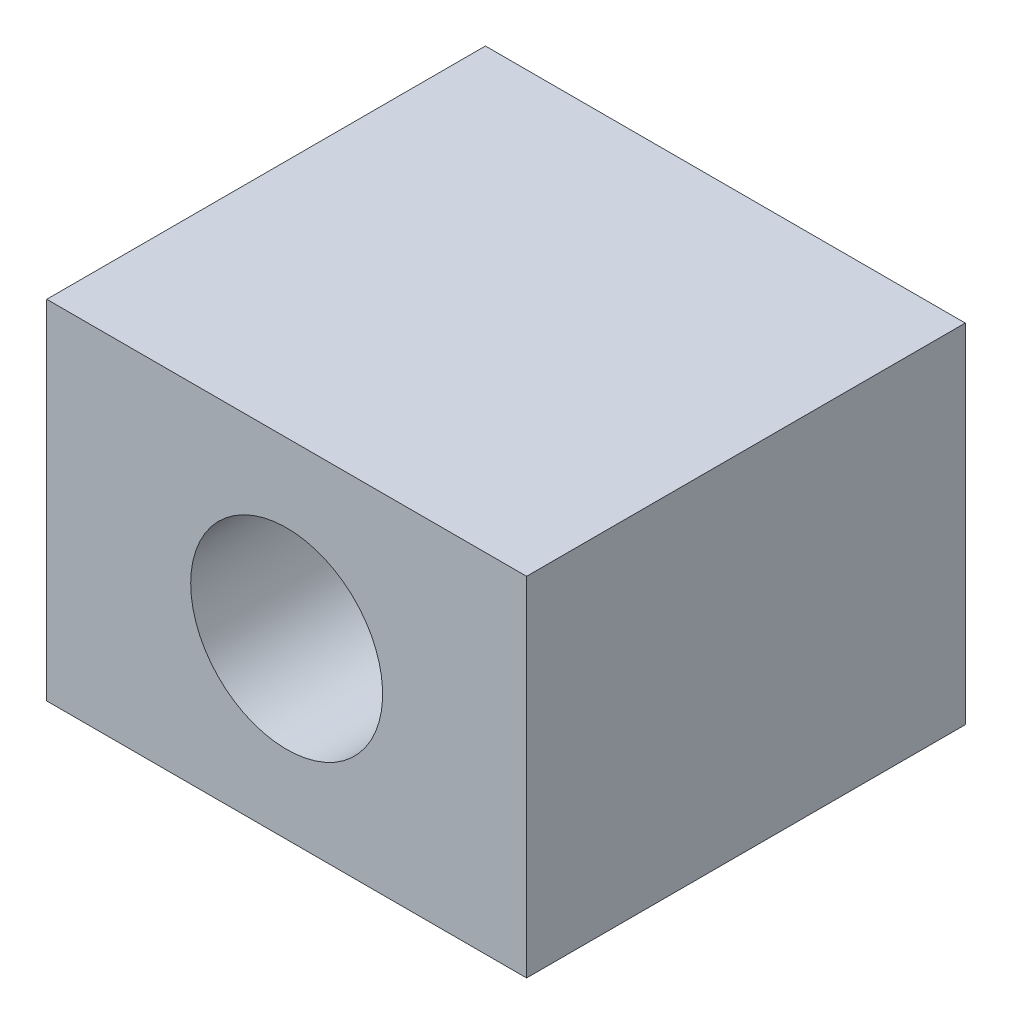
SolidWorks part; units mm, degrees
ref_plane "前视基准面" through (0, 0, 0) normal (0, 0, 1) x (1, 0, 0)
ref_plane "上视基准面" through (0, 0, 0) normal (0, 1, 0) x (1, 0, 0)
ref_plane "右视基准面" through (0, 0, 0) normal (1, 0, 0) x (0, 0, -1)
sketch "草图1" plane through (0, 0, 0) normal (0, 1, 0) x (1, 0, 0)
  circle A0 centre (0, 0) radius 15
  dimension "D1" = 30
extrude "凸台-拉伸1" add sketch "草图1" along normal blind 5
sketch "草图2" plane through (0, 5, 0) normal (0, 1, 0) x (1, 0, 0)
  circle A0 centre (0, 0) radius 12 construction
  point P4 (0, 12)
  point P6 (0, -12)
  point P8 (-12, 0)
  point P10 (12, 0)
  dimension "D1" = 24
hole_wizard "M3 螺纹孔的螺纹孔钻头1" positions "草图2" profile "草图3" hole size "M3" standard "GB" end condition up to next
sketch "草图3" plane through (12, 5, 0) normal (1, 0, 0) x (0, 0, 1)
  line L0 (0, 0) -> (0, 5)
  line L1 (0, 5) -> (1.25, 5)
  line L2 (1.25, 5) -> (1.25, 0)
  line L5 (1.25, 0) -> (0, 0)
  line L11 (0, -6.35) -> (0, 107.95) construction
  dimension "通孔孔直径" = 2.5
  dimension "通孔孔深度" = 5
sketch "草图4" plane through (0, 5, 0) normal (0, 1, 0) x (1, 0, 0)
  circle A0 centre (0, 0) radius 6
  dimension "D1" = 12
extrude "凸台-拉伸2" add sketch "草图4" along normal blind 10
sketch "草图5" plane through (0, 15, 0) normal (0, 1, 0) x (1, 0, 0)
  circle A0 centre (0, 0) radius 2.5
  dimension "D1" = 5
extrude "切除-拉伸1" cut sketch "草图5" against normal through all
fillet "圆角1" radius 0.5 1 edges at (0, 5, 6)
sketch "草图6" plane through (0, 0, 0) normal (0, 0, 1) x (1, 0, 0)
  line L0 (-2, 8.1) -> (2, 8.1)
  line L1 (2, 8.1) -> (2, 11)
  line L2 (2, 11) -> (-2, 11)
  line L3 (0, 11) -> (0, 8.1) construction
  line L5 (2.5, 15) -> (-2.5, 15) construction
  line L7 (-2, 8.1) -> (-2, 11)
  dimension "D1" = 2
  dimension "D2" = 2.9
  dimension "D3" = 4
extrude "切除-拉伸3" cut sketch "草图6" against normal through all flip side to cut contours L1 L2 L7 L0
sketch "草图7" plane through (0, 11, 0) normal (0, 1, 0) x (1, 0, 0)
  line L0 (2, 1.5) -> (-2, 1.5)
  line L1 (-2, 1.5) -> (-2, 2.8083)
  line L2 (-2, 5.6569) -> (-2, 1.5) construction
  line L3 (-2, 2.8083) -> (2, 2.8083)
  line L4 (2, 5.6569) -> (2, 1.5) construction
  line L5 (2, 2.8083) -> (2, 1.5)
  line L6 (0, 1.5) -> (0, 2.8083) construction
  dimension "D1" = 1.5
  dimension "D2" = 1.3083
  dimension "D3" = 1.3083
extrude "凸台-拉伸3" add sketch "草图7" against normal through all contours L3 L5 L0 L1
sketch "草图9" plane through (0, 0, -1.5) normal (0, 0, 1) x (1, 0, 0)
  line L0 (2, 8.1) -> (-2, 11) construction
  line L1 (2, 11) -> (-2, 8.1) construction
hole_wizard "M2 螺纹孔的螺纹孔钻头1" positions "草图10" profile "草图11" hole size "M2" standard "GB" end condition through all
sketch "草图10" plane through (0, 0, -1.5) normal (0, 0, 1) x (1, 0, 0)
  line L0 (2, 8.1) -> (-2, 11) construction
  point P1 (0, 9.55)
sketch "草图11" plane through (0, 9.55, -1.5) normal (1, 0, 0) x (0, -1, 0)
  line L0 (0, 0) -> (0, 4.5)
  line L1 (0, 4.5) -> (0.8, 4.5)
  line L2 (0.8, 4.5) -> (0.8, 0)
  line L5 (0.8, 0) -> (0, 0)
  line L11 (0, -6.35) -> (0, 107.95) construction
  dimension "通孔孔直径" = 1.6
  dimension "通孔孔深度" = 4.5
sketch "草图12" plane through (0, 8.1, 0) normal (0, -1, 0) x (1, 0, 0)
  line L1 (-2, -1.5) -> (2, -1.5)
  line L2 (-2, -1.5) -> (-2, -5.6569)
  line L3 (-2, -5.6569) -> (2, -5.6569)
  line L4 (2, -1.5) -> (2, -5.6569)
extrude "切除-拉伸4" cut sketch "草图12" against normal through all flip side to cut
sketch "草图13" plane through (0, 8.1, 0) normal (0, -1, 0) x (1, 0, 0)
  line L0 (2, -5.6569) -> (2, -1.5) construction
  line L1 (-2, -1.5) -> (2, -1.5)
  line L2 (-2, -1.5) -> (-2, -2)
  line L3 (-2, -2) -> (2, -2)
  line L4 (2, -1.5) -> (2, -2)
  dimension "D1" = 0.5
extrude "切除-拉伸5" cut sketch "草图13" against normal through all
